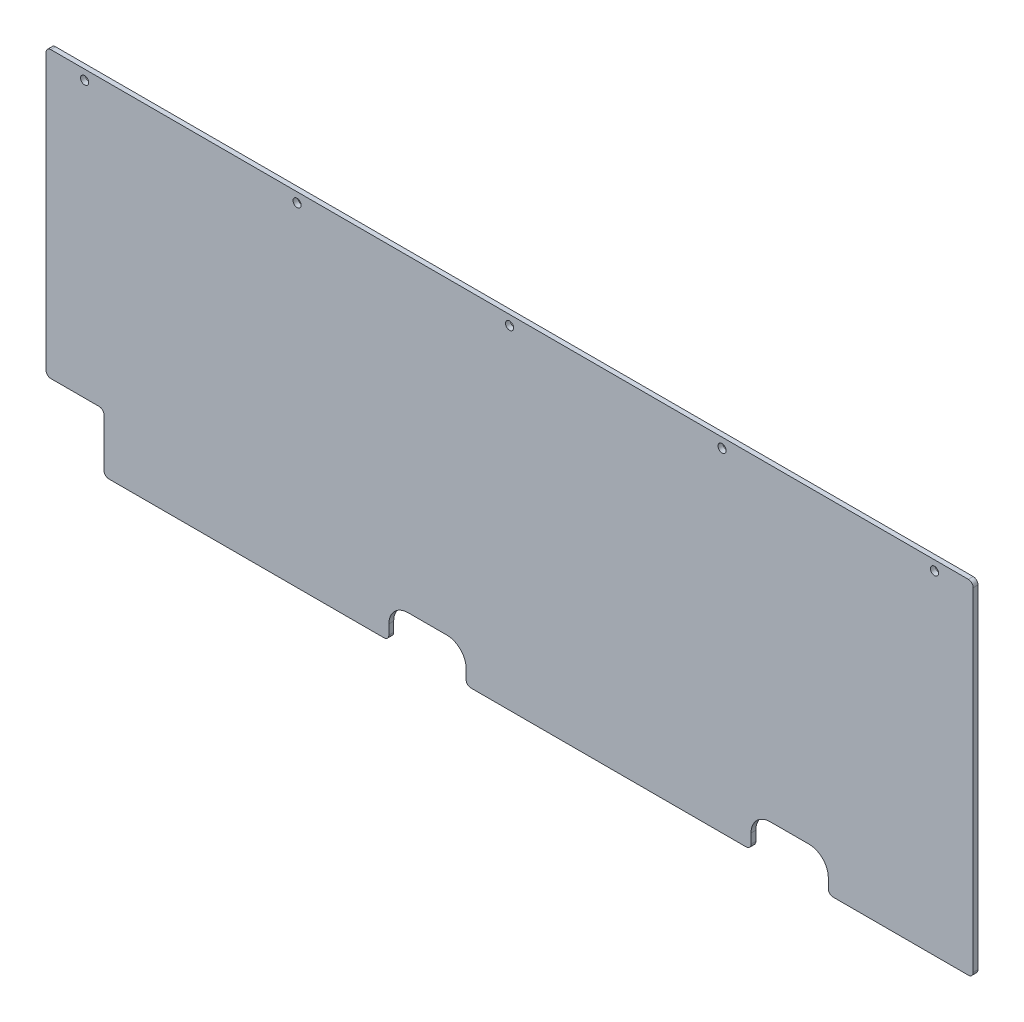
SolidWorks part; units mm, degrees
ref_plane "Front Plane" through (0, 0, 0) normal (0, 0, 1) x (1, 0, 0)
ref_plane "Top Plane" through (0, 0, 0) normal (0, 1, 0) x (1, 0, 0)
ref_plane "Right Plane" through (0, 0, 0) normal (1, 0, 0) x (0, 0, -1)
sketch "Sketch1" plane through (0, 0, 0) normal (0, 0, 1) x (1, 0, 0)
  line L1 (0, 0) -> (1219.2, 0)
  line L2 (0, 0) -> (0, 450.85)
  line L3 (0, 450.85) -> (1219.2, 450.85)
  line L4 (1219.2, 0) -> (1219.2, 450.85)
  dimension "D1" = 1219.2
  dimension "D2" = 450.85
extrude "Boss-Extrude1" add sketch "Sketch1" along normal blind 6.35
sketch "Sketch2" plane through (0, 0, 6.35) normal (0, 0, 1) x (1, 0, 0)
  line L0 (450.85, 19.05) -> (450.85, 0)
  line L1 (0, 0) -> (1219.2, 0) construction
  line L2 (450.85, 0) -> (552.45, 0)
  line L3 (552.45, 0) -> (552.45, 19.05)
  line L5 (476.25, 44.45) -> (527.05, 44.45)
  line L6 (0, 450.85) -> (0, 0) construction
  arc A1 (552.45, 19.05) -> (527.05, 44.45) centre (527.05, 19.05) ccw
  arc A2 (476.25, 44.45) -> (450.85, 19.05) centre (476.25, 19.05) ccw
  dimension "D1" = 101.6
  dimension "D4" = 25.4
  dimension "D5" = 25.4
  dimension "D2" = 450.85
  dimension "D3" = 44.45
extrude "Cut-Extrude1" cut sketch "Sketch2" against normal through all
pattern_linear "LPattern1" count 2 spacing 476.25 along (1, 0, 0) of "Cut-Extrude1"
sketch "Sketch3" plane through (0, 0, 6.35) normal (0, 0, 1) x (1, 0, 0)
  line L1 (0, 0) -> (76.2, 0)
  line L2 (0, 0) -> (0, 76.2)
  line L3 (0, 76.2) -> (76.2, 76.2)
  line L4 (76.2, 0) -> (76.2, 76.2)
  dimension "D1" = 76.2
  dimension "D2" = 76.2
extrude "Cut-Extrude2" cut sketch "Sketch3" against normal through all
fillet "Fillet1" radius 6.35 1 edges at (76.2, 76.2, 3.175)
hole_wizard "27/64 (0.42188) Diameter Hole1" positions "Sketch4" profile "Sketch5" hole size "27/64" standard "ANSI Inch" end condition up to next
sketch "Sketch4" plane through (0, 0, 6.35) normal (0, 0, 1) x (1, 0, 0)
  line L0 (0, 450.85) -> (0, 76.2) construction
  line L1 (1219.2, 450.85) -> (0, 450.85) construction
  point P0 (50.8, 438.15)
  point P2 (330.2, 438.15)
  point P4 (609.6, 438.15)
  point P6 (889, 438.15)
  point P8 (1168.4, 438.15)
  dimension "D1" = 50.8
  dimension "D2" = 279.4
  dimension "D3" = 279.4
  dimension "D4" = 279.4
  dimension "D5" = 279.4
  dimension "D6" = 12.7
sketch "Sketch5" plane through (50.8, 438.15, 6.35) normal (1, 0, 0) x (0, -1, 0)
  line L0 (0, 0) -> (0, 6.35)
  line L1 (0, 6.35) -> (5.3579, 6.35)
  line L2 (5.3579, 6.35) -> (5.3579, 0)
  line L5 (5.3579, 0) -> (0, 0)
  line L11 (0, -6.35) -> (0, 107.95) construction
  dimension "Thru Hole Dia." = 10.7158
  dimension "Thru Hole Depth" = 6.35
fillet "Fillet2" radius 6.35 9 edges at (1219.2, 450.85, 3.175) (1219.2, 0, 3.175) (1028.7, 0, 3.175) (927.1, 0, 3.175) (552.45, 0, 3.175) (450.85, 0, 3.175) (76.2, 0, 3.175) (0, 76.2, 3.175) (0, 450.85, 3.175)
